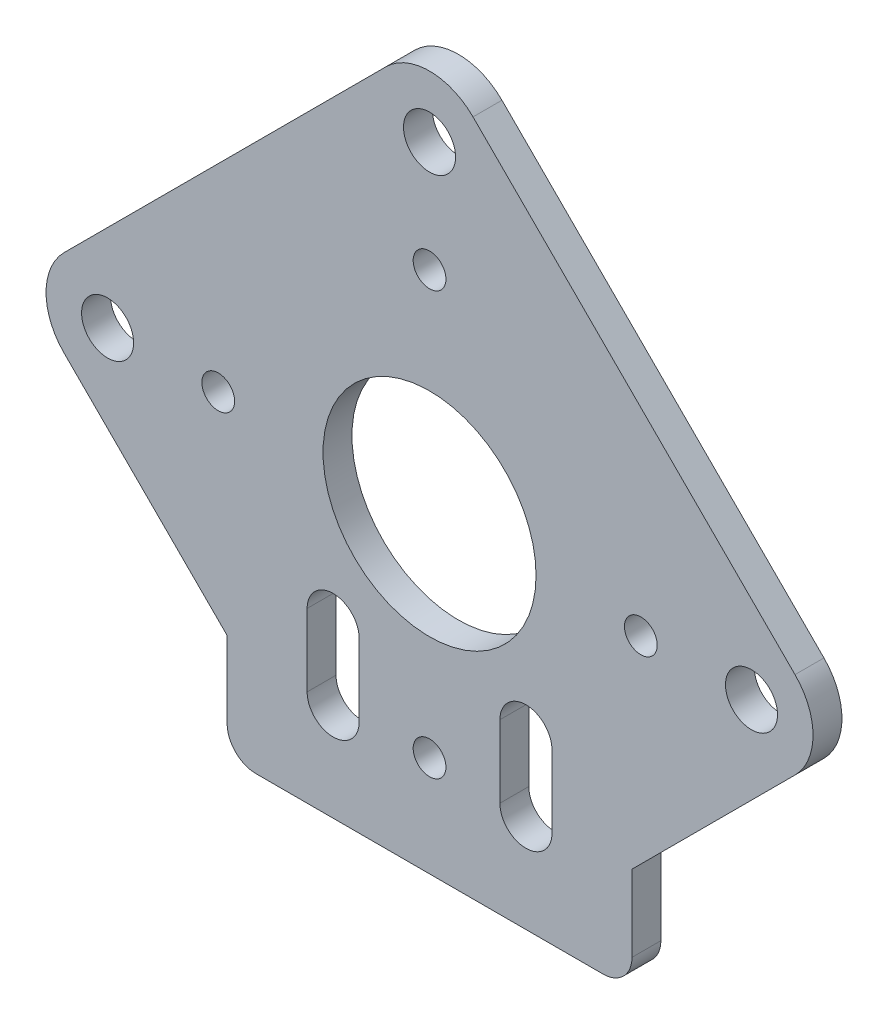
SolidWorks part; units mm, degrees
ref_plane "Ebene vorne" through (0, 0, 0) normal (0, 0, 1) x (1, 0, 0)
ref_plane "Ebene oben" through (0, 0, 0) normal (0, 1, 0) x (1, 0, 0)
ref_plane "Ebene rechts" through (0, 0, 0) normal (1, 0, 0) x (0, 0, -1)
sketch "Model" plane through (0, 0, 0) normal (0, 0, 1) x (1, 0, 0)
  line L0 (19, 10.9236) -> (19, 3)
  line L1 (22, 0) -> (58, 0)
  line L2 (61, 3) -> (61, 10.9236)
  line L3 (32.7, 10) -> (32.7, 17.5)
  line L4 (27.3, 17.5) -> (27.3, 10)
  line L5 (47.3, 10) -> (47.3, 17.5)
  line L6 (52.7, 17.5) -> (52.7, 10)
  line L7 (61, 10.9236) -> (77.9151, 27.8387)
  line L8 (77.9151, 36.8613) -> (44.5113, 70.2651)
  line L9 (35.4887, 70.2651) -> (2.0849, 36.8613)
  line L10 (2.0849, 27.8387) -> (19, 10.9236)
  circle A0 centre (40, 10.4297) radius 1.7
  circle A1 centre (61.9203, 32.35) radius 1.7
  circle A2 centre (40, 54.2703) radius 1.7
  circle A3 centre (18.0797, 32.35) radius 1.7
  circle A4 centre (40, 32.35) radius 11.05
  circle A5 centre (73.4, 32.35) radius 2.7
  circle A6 centre (40, 65.75) radius 2.7
  circle A7 centre (6.6, 32.35) radius 2.7
  arc A8 (77.9151, 27.8387) -> (77.9151, 36.8613) centre (73.4037, 32.35) ccw
  arc A9 (44.5113, 70.2651) -> (35.4887, 70.2651) centre (40, 65.7537) ccw
  arc A10 (2.0849, 36.8613) -> (2.0849, 27.8387) centre (6.5963, 32.35) ccw
  arc A11 (19, 3) -> (22, 0) centre (22, 3) ccw
  arc A12 (58, 0) -> (61, 3) centre (58, 3) ccw
  arc A13 (32.7, 17.5) -> (27.3, 17.5) centre (30, 17.5) ccw
  arc A14 (27.3, 10) -> (32.7, 10) centre (30, 10) ccw
  arc A15 (52.7, 17.5) -> (47.3, 17.5) centre (50, 17.5) ccw
  arc A16 (47.3, 10) -> (52.7, 10) centre (50, 10) ccw
extrude "Aufsatz-Linear austragen1" add sketch "Model" along normal blind 3
